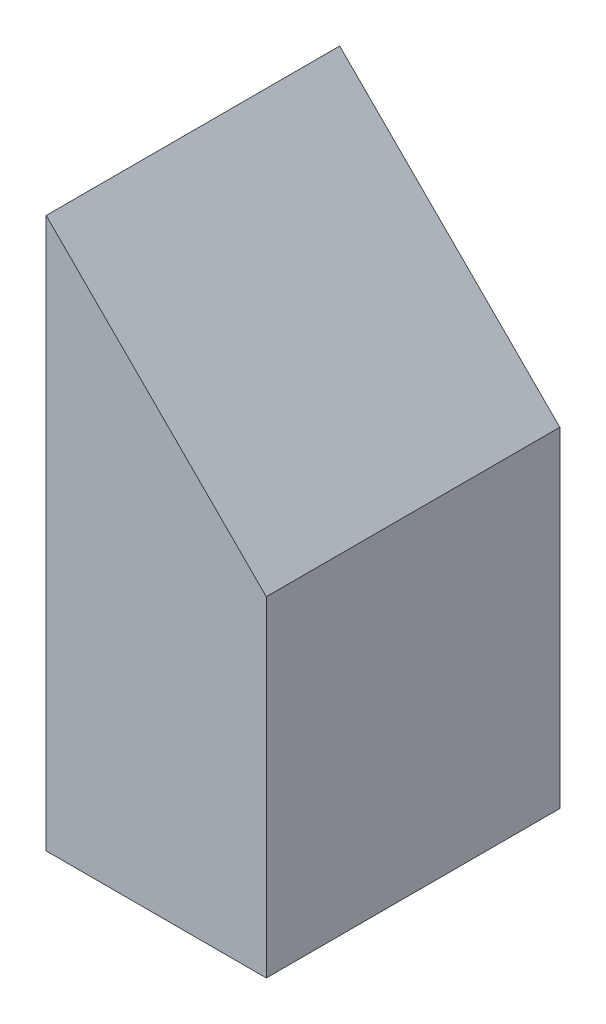
SolidWorks part; units mm, degrees
ref_plane "Front Plane" through (0, 0, 0) normal (0, 0, 1) x (1, 0, 0)
ref_plane "Top Plane" through (0, 0, 0) normal (0, 1, 0) x (1, 0, 0)
ref_plane "Right Plane" through (0, 0, 0) normal (1, 0, 0) x (0, 0, -1)
sketch "Sketch1" plane through (0, 0, 0) normal (0, 1, 0) x (1, 0, 0)
  line L0 (19.05, 25.4) -> (-19.05, 25.4)
  line L1 (-19.05, 25.4) -> (-19.05, -25.4)
  line L2 (-19.05, -25.4) -> (19.05, -25.4)
  line L3 (19.05, -25.4) -> (19.05, 25.4)
  line L4 (-19.05, 25.4) -> (19.05, -25.4) construction
  dimension "D1" = 50.8
  dimension "D2" = 38.1
extrude "Boss-Extrude1" add sketch "Sketch1" along normal blind 95.25
sketch "Sketch2" plane through (0, 0, 0) normal (0, 0, 1) x (1, 0, 0)
  line L0 (-19.05, 95.25) -> (19.05, 57.15)
  line L1 (19.05, 95.25) -> (19.05, 0) construction
  line L2 (-19.05, 95.25) -> (-19.05, 0) construction
  dimension "D1" = 45
extrude "Cut-Extrude1" cut sketch "Sketch2" against normal through all and the other way through all
